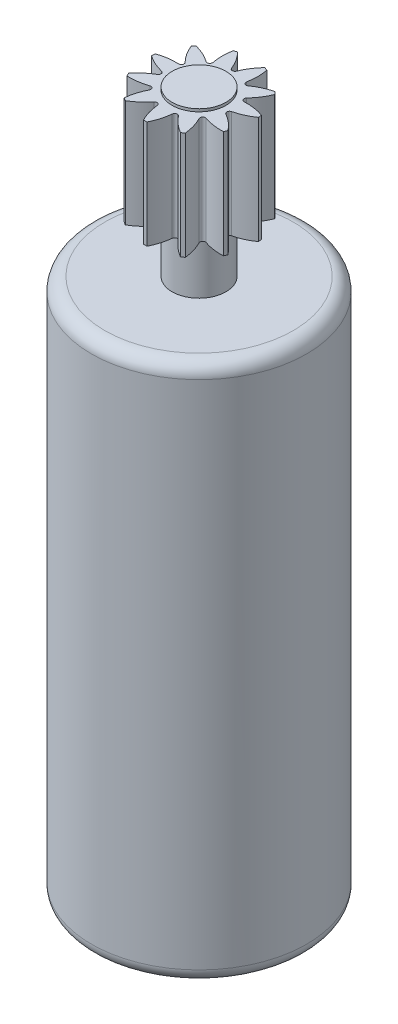
SolidWorks part; units mm, degrees
ref_plane "Front Plane" through (0, 0, 0) normal (0, 0, 1) x (1, 0, 0)
ref_plane "Top Plane" through (0, 0, 0) normal (0, 1, 0) x (1, 0, 0)
ref_plane "Right Plane" through (0, 0, 0) normal (1, 0, 0) x (0, 0, -1)
sketch "Sketch1" plane through (0, 0, 0) normal (0, 0, 1) x (1, 0, 0)
  line L0 (0, 0) -> (0, 26.1)
  line L1 (0, 0) -> (4, 0)
  line L2 (4, 0) -> (4, 20)
  line L3 (4, 20) -> (1, 20)
  line L4 (1, 20) -> (1, 22)
  line L5 (1, 22) -> (2, 22)
  line L6 (2, 22) -> (2, 26)
  line L7 (2, 26) -> (1, 26)
  line L8 (1, 26) -> (1, 26.1)
  line L9 (1, 26.1) -> (0, 26.1)
  dimension "D1" = 26.1
  dimension "D2" = 4
  dimension "D3" = 20
  dimension "D4" = 3
  dimension "D5" = 2
  dimension "D6" = 1
  dimension "D7" = 4
revolve "Revolve1" add sketch "Sketch1" angle 360 about L0
fillet "Fillet1" radius 0.5 2 edges at (0, 20, -4) (0, 0, -4)
sketch "Sketch2" plane through (0, 26, 0) normal (0, 1, 0) x (1, 0, 0)
  line L0 (0, 0) -> (0, 2.9979) construction
  circle A0 centre (0, 0) radius 2 construction
  arc A1 (0.5, 1.9365) -> (-0.5, 1.9365) centre (0, 0) ccw
  arc A2 (-0.5, 1.9365) -> (-0.0929, 1.2999) centre (-1.951, 0.5601) cw
  circle A3 centre (0, 0) radius 1 construction
  arc A4 (0.5, 1.9365) -> (0.0929, 1.2999) centre (1.951, 0.5601) ccw
  arc A5 (-0.0929, 1.2999) -> (0.0929, 1.2999) centre (0, 1.3369) ccw
  point P15 (0, 1)
  dimension "D2" = 2
  dimension "D3" = 2
  dimension "D4" = 0.1
  dimension "D1" = 1
extrude "Cut-Extrude1" cut sketch "Sketch2" against normal up to next
pattern_circular "CirPattern1" count 11 over 360 about axis through (0, 0, 0) along (0, 1, 0) of "Cut-Extrude1"
